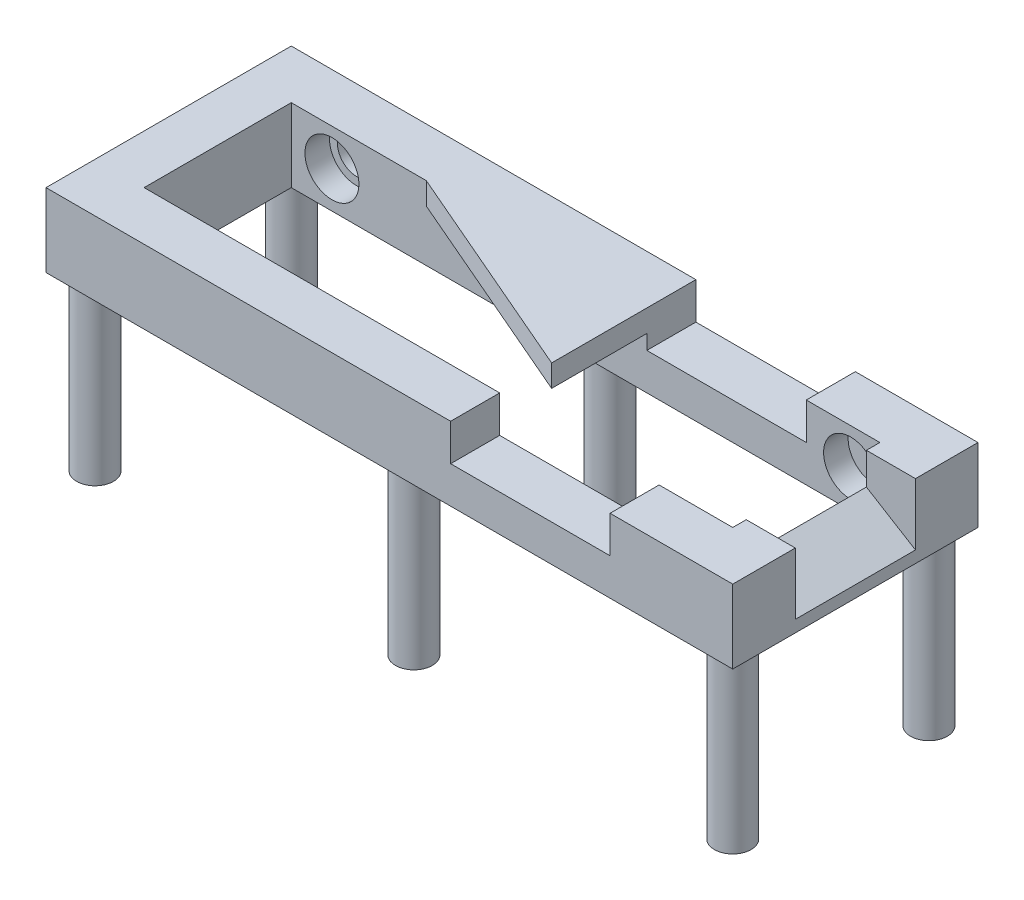
SolidWorks part; units mm, degrees
ref_plane "Ön Düzlem" through (0, 0, 0) normal (0, 0, 1) x (1, 0, 0)
ref_plane "Üst Düzlem" through (0, 0, 0) normal (0, 1, 0) x (1, 0, 0)
ref_plane "Sağ Düzlem" through (0, 0, 0) normal (1, 0, 0) x (0, 0, -1)
sketch "Çizim1" plane through (0, 0, 0) normal (0, 1, 0) x (1, 0, 0)
  line L0 (-20, 80) -> (260, 80)
  line L1 (0, 0) -> (240, 0)
  line L2 (0, 0) -> (0, 60)
  line L3 (0, 60) -> (240, 60)
  line L4 (240, 0) -> (240, 60)
  line L5 (260, -20) -> (260, 80)
  line L6 (-20, -20) -> (260, -20)
  line L7 (-20, -20) -> (-20, 80)
  dimension "D1" = 60
  dimension "D2" = 240
  dimension "D3" = 20
extrude "Yükseklik-Ekstrüzyon1" add sketch "Çizim1" along normal blind 30
sketch "Çizim2" plane through (0, 0, 0) normal (0, -1, 0) x (-1, 0, 0)
  line L0 (0, 0) -> (20, -20) construction
  line L1 (15, -20) -> (15, 9.3947) construction
  line L2 (20, -20) -> (-260, -20) construction
  line L3 (20, -15) -> (0, -15) construction
  line L4 (20, 80) -> (20, -20) construction
  line L5 (-120, -20) -> (-120, 658.3884) construction
  line L6 (-240, 30) -> (0, 30) construction
  line L7 (-240, 0) -> (-240, 60) construction
  line L8 (0, 60) -> (0, 0) construction
  circle A0 centre (10, -10) radius 7.5
  circle A1 centre (-250, -10) radius 7.5
  circle A2 centre (10, 70) radius 7.5
  circle A3 centre (-250, 70) radius 7.5
  circle A4 centre (-120, -10) radius 7.5
  circle A5 centre (-120, 70) radius 7.5
  dimension "D1" = 15
  dimension "D2" = 15
  dimension "D3" = 15
extrude "Yükseklik-Ekstrüzyon2" add sketch "Çizim2" along normal blind 70
sketch "Çizim3" plane through (0, 0, 20) normal (0, 0, 1) x (1, 0, 0)
  line L0 (-20, 15) -> (37.6853, 15) construction
  line L1 (-20, 30) -> (-20, 0) construction
  line L2 (120, 30) -> (120, -4.2908) construction
  line L3 (-20, 30) -> (260, 30) construction
  circle A0 centre (16.5795, 15) radius 11
  circle A1 centre (228.0369, 15) radius 11
  circle A2 centre (95.4699, 15) radius 11
  dimension "D1" = 22
ref_plane "Düzlem1" through (0, 0, -30) normal (0, 0, 1) x (1, 0, 0)
sketch "Çizim4" plane through (0, 0, -30) normal (0, 0, 1) x (1, 0, 0)
  circle A0 centre (228.0369, 15) radius 11
  circle A1 centre (16.5795, 15) radius 11
  circle A2 centre (95.4699, 15) radius 11
extrude "Kes-Ekstrüzyon1" cut sketch "Çizim4" against normal mid plane 80
sketch "Çizim5" plane through (0, 0, 20) normal (0, 0, 1) x (1, 0, 0)
  line L0 (144.9782, 30) -> (144.9782, 15)
  line L1 (-20, 30) -> (260, 30) construction
  line L2 (-20, 15) -> (37.6853, 15) construction
  line L3 (144.9782, 15) -> (209.9782, 15)
  line L4 (209.9782, 15) -> (209.9782, 30)
  line L6 (144.9782, 30) -> (209.9782, 30)
  dimension "D1" = 65
extrude "Kes-Ekstrüzyon2" cut sketch "Çizim5" against normal blind 119 contours L3 L4 L6 L0
sketch "Çizim6" plane through (0, 0, -30) normal (0, 0, 1) x (1, 0, 0)
  line L0 (234.3599, 20.4676) -> (260, 4.8011)
  line L1 (260, 4.8011) -> (234.3599, 20.4676)
  line L2 (260, 4.8011) -> (260, 31.5523)
  line L3 (260, 31.5523) -> (234.1332, 31.5523)
  line L4 (234.1332, 31.5523) -> (234.3599, 20.4676)
  line L5 (260, 30) -> (260, 0) construction
extrude "Kes-Ekstrüzyon3" cut sketch "Çizim6" against normal mid plane 49 contours L3 L4 L0 L2
sketch "Çizim7" plane through (0, 0, -30) normal (0, 0, 1) x (1, 0, 0)
  circle A0 centre (228.0369, 15) radius 4
  circle A1 centre (95.4699, 15) radius 4
  dimension "D1" = 8
  dimension "D2" = 8
ref_plane "Düzlem2" through (0, 22, 0) normal (0, 1, 0) x (1, 0, 0)
sketch "Çizim10" plane through (0, 22, 0) normal (0, 1, 0) x (1, 0, 0)
  line L0 (55.057, 60) -> (144.9782, 21.1759)
  line L1 (144.9782, 60) -> (0, 60) construction
  line L3 (144.9782, 21.1759) -> (144.9782, 60)
  line L4 (144.9782, 60) -> (55.057, 60)
  line L5 (0, 0) -> (144.9782, 0) construction
  dimension "D1" = 21.1759
extrude "Yükseklik-Ekstrüzyon4" add sketch "Çizim10" along normal blind 8 and the other way blind 1
sketch "Çizim13" plane through (0, 0, -80) normal (0, 0, -1) x (-1, 0, 0)
  circle A0 centre (-16.5795, 15) radius 7.75
  dimension "D1" = 15.5
extrude "Kes-Ekstrüzyon4" cut sketch "Çizim13" against normal blind 18
